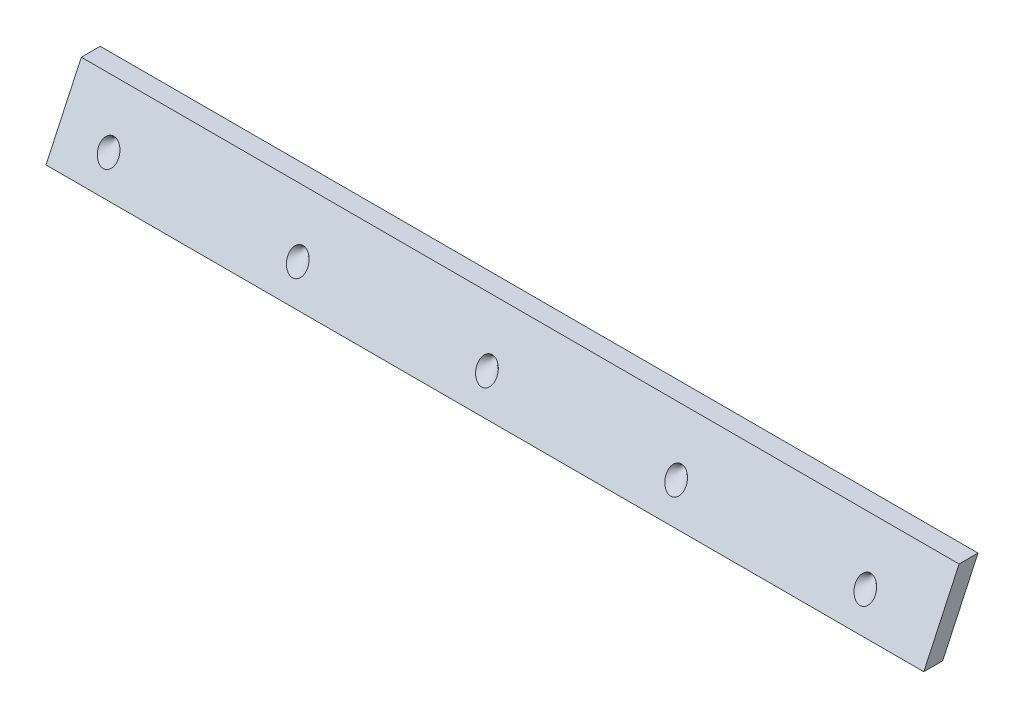
SolidWorks part; units mm, degrees
ref_plane "Front Plane" through (0, 0, 0) normal (0, 0, 1) x (1, 0, 0)
ref_plane "Top Plane" through (0, 0, 0) normal (0, 1, 0) x (1, 0, 0)
ref_plane "Right Plane" through (0, 0, 0) normal (1, 0, 0) x (0, 0, -1)
sketch "Sketch1" plane through (0, 0, 0) normal (1, 0, 0) x (0, 0, -1)
  line L0 (0, 0) -> (9.3262, 20)
  line L1 (0, 0) -> (-5, 0)
  line L2 (9.3262, 20) -> (4.3262, 20)
  line L3 (-5, 0) -> (4.3262, 20)
  line L4 (0, 0) -> (11.8289, 0) construction
  dimension "D1" = 5
  dimension "D2" = 65
  dimension "D3" = 20
extrude "Boss-Extrude1" add sketch "Sketch1" along normal mid plane 232 contours L3 L2 L0 L1
ref_plane "Plane1" through (-103, 0, 0) normal (-1, 0, 0) x (0, 0, 1)
sketch "Sketch3" plane through (-103, 0, 0) normal (-1, 0, 0) x (0, 0, 1)
  line L0 (9.024, 9) -> (-13.587, 9) construction
  line L1 (0, 0) -> (5, 0) construction
  line L3 (-1.5444, 9) -> (2.8545, 4.6011)
  line L4 (2.8545, 4.6011) -> (0.8032, 9)
  line L5 (5, 0) -> (-4.3262, 20) construction
  line L6 (-1.5444, 9) -> (0.8032, 9)
  line L7 (0.8032, 9) -> (0.0566, 10.6011) construction
  line L8 (0.0566, 10.6011) -> (-1.5444, 9) construction
  dimension "D1" = 9
  dimension "D2" = 45
  dimension "D3" = 6
  dimension "D4" = 90
revolve "Cut-Revolve1" cut sketch "Sketch3" angle 360 about L0
pattern_linear "LPattern1" count 5 spacing 50 along (1, 0, 0) of "Cut-Revolve1"
